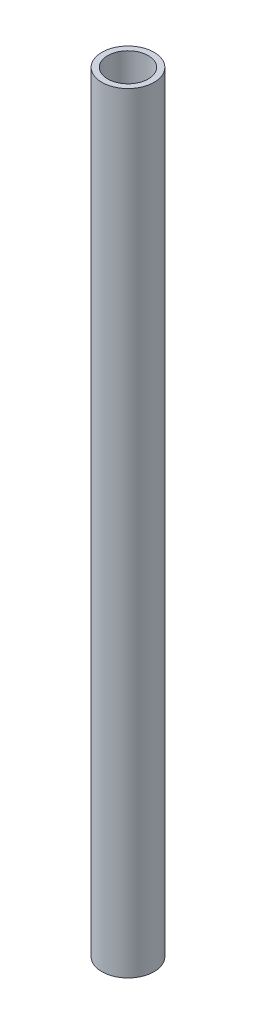
SolidWorks part; units mm, degrees
ref_plane "Front Plane" through (0, 0, 0) normal (0, 0, 1) x (1, 0, 0)
ref_plane "Top Plane" through (0, 0, 0) normal (0, 1, 0) x (1, 0, 0)
ref_plane "Right Plane" through (0, 0, 0) normal (1, 0, 0) x (0, 0, -1)
sketch "Sketch1" plane through (0, 0, 0) normal (0, 1, 0) x (1, 0, 0)
  circle A0 centre (0, 0) radius 7
  circle A1 centre (0, 0) radius 9
  dimension "D1" = 14
  dimension "D2" = 18
extrude "Boss-Extrude1" add sketch "Sketch1" along normal blind 265.82
